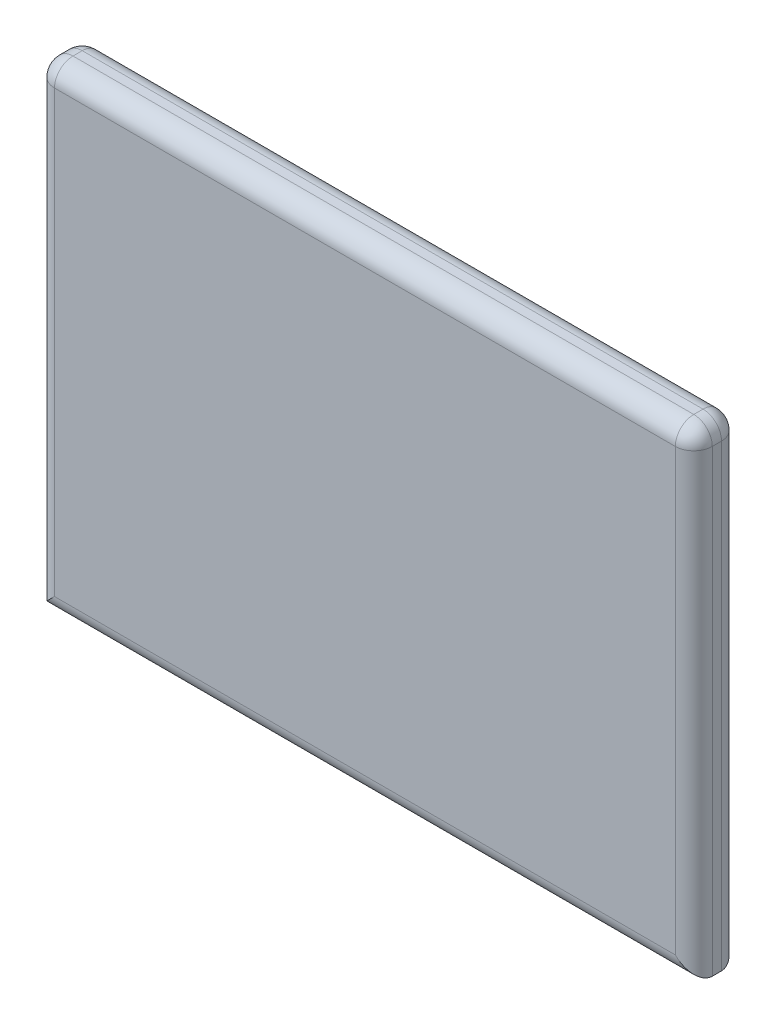
SolidWorks part; units mm, degrees
ref_plane "Plan de face" through (0, 0, 0) normal (0, 0, 1) x (1, 0, 0)
ref_plane "Plan de dessus" through (0, 0, 0) normal (0, 1, 0) x (1, 0, 0)
ref_plane "Plan de droite" through (0, 0, 0) normal (1, 0, 0) x (0, 0, -1)
sketch "Esquisse1" plane through (0, 0, 0) normal (0, 0, 1) x (1, 0, 0)
  line L0 (0, 129.17) -> (0, -344.0928) construction
  line L1 (-178, 129.17) -> (178, 129.17)
  line L2 (-178, 129.17) -> (-178, -129.17)
  line L3 (-178, -129.17) -> (178, -129.17)
  line L4 (178, 129.17) -> (178, -129.17)
  line L5 (0, 0) -> (-556.8702, 0) construction
  dimension "D1" = 356
  dimension "D2" = 258.34
extrude "Boss.-Extru.1" add sketch "Esquisse1" along normal blind 25
fillet "Congé1" radius 10 10 edges at (178, 0, 0) (0, -129.17, 0) (0, -129.17, 25) (0, 129.17, 25) (0, 129.17, 0) (-178, 0, 0) (-178, 0, 25) (178, 0, 25) (178, 129.17, 12.5) (-178, 129.17, 12.5)
ref_plane "Plan1" through (120, 0, 0) normal (1, 0, 0) x (0, 0, -1)
sketch "Esquisse3" plane through (120, 0, 0) normal (1, 0, 0) x (0, 0, -1)
  line L0 (0, 119.17) -> (0, -119.17) construction
  line L1 (0, 119.17) -> (0, -119.17) construction
  line L2 (-15, 129.17) -> (-10, 129.17) construction
  line L4 (0, 101.1779) -> (0, 79.0661)
  line L6 (8.0193, 101.1779) -> (8.0193, 79.0661) construction
  line L7 (-15, 129.17) -> (-10, 129.17) construction
  line L8 (8.0193, 90.122) -> (-13.1089, 90.122) construction
  spline S0 degree 3 poles (0, 101.1779) (8.0124, 104.4204) (5.5113, 94.6601) (8.0193, 90.122) knots 0 0 0 0 1 1 1 1
  spline S1 degree 3 poles (0, 79.0661) (8.0124, 75.8236) (5.5113, 85.5839) (8.0193, 90.122) knots 0 0 0 0 1 1 1 1
extrude "Boss.-Extru.2" add sketch "Esquisse3" along normal blind 35
mirror "Symétrie1" about plane through (0, 0, 0) normal (1, 0, 0) of "Boss.-Extru.2"
sketch "Esquisse4" plane through (0, -129.17, 0) normal (0, -1, 0) x (1, 0, 0)
  line L1 (-100, 16.5) -> (100, 16.5)
  line L2 (-100, 16.5) -> (-100, 8.5)
  line L3 (-100, 8.5) -> (100, 8.5)
  line L4 (100, 16.5) -> (100, 8.5)
  line L5 (0, 0) -> (0, 90.4363) construction
  line L6 (-178, 12.5) -> (201.1757, 12.5) construction
  line L7 (-178, 15) -> (-178, 10) construction
  dimension "D1" = 200
  dimension "D2" = 8
extrude "Enlèv. mat.-Extru.1" cut sketch "Esquisse4" against normal blind 3
